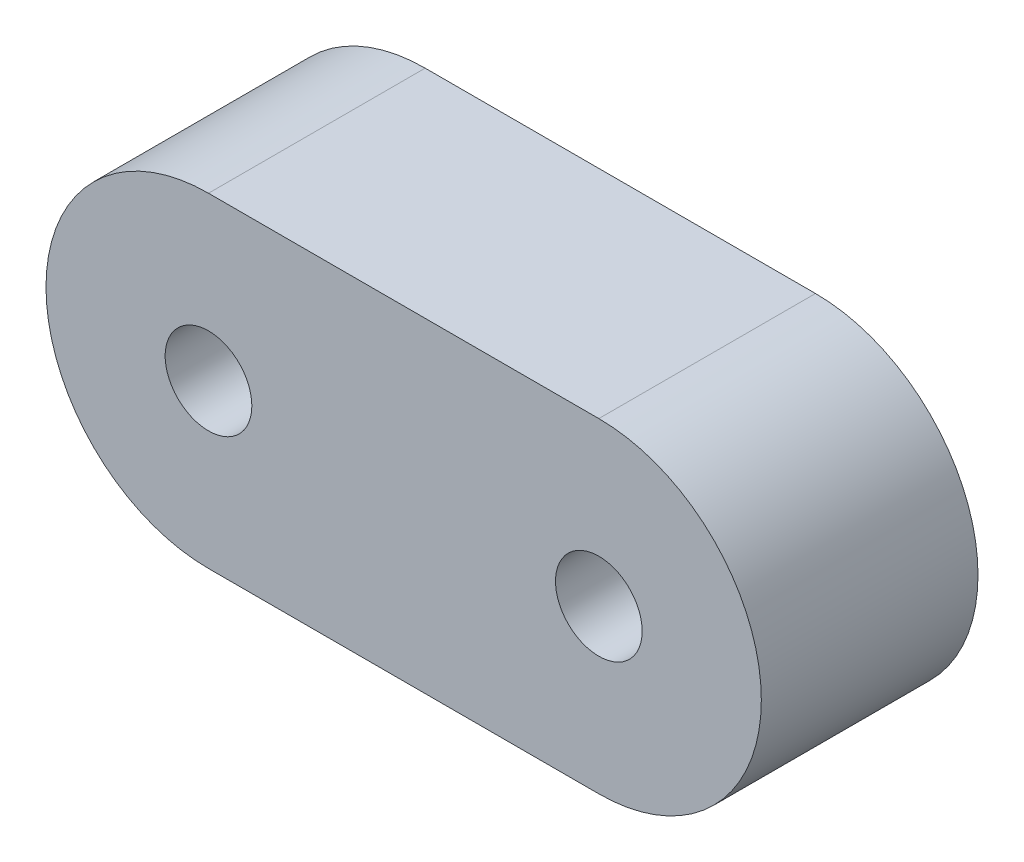
SolidWorks part; units mm, degrees
ref_plane "前视基准面" through (0, 0, 0) normal (0, 0, 1) x (1, 0, 0)
ref_plane "上视基准面" through (0, 0, 0) normal (0, 1, 0) x (1, 0, 0)
ref_plane "右视基准面" through (0, 0, 0) normal (1, 0, 0) x (0, 0, -1)
other "Configuration Table"
sketch "草图1" plane through (0, 0, 0) normal (0, 0, 1) x (1, 0, 0)
  line L0 (0, 15) -> (36.03, 15)
  line L1 (0, -15) -> (36.03, -15)
  arc A0 (0, 15) -> (0, -15) centre (0, 0) ccw
  arc A1 (36.03, -15) -> (36.03, 15) centre (36.03, 0) ccw
  circle A2 centre (0, 0) radius 4
  circle A3 centre (36.03, 0) radius 4
  point P1 (0, 0)
extrude "凸台-拉伸1" add sketch "草图1" along normal blind 20
